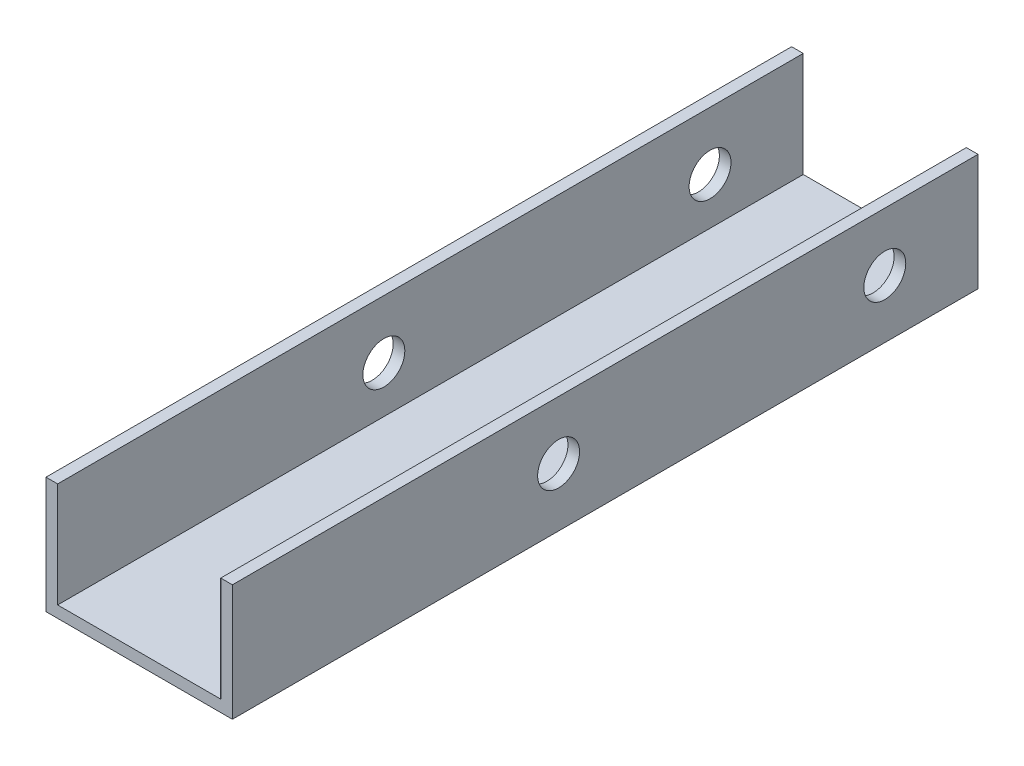
SolidWorks part; units mm, degrees
ref_plane "Ön Düzlem" through (0, 0, 0) normal (0, 0, 1) x (1, 0, 0)
ref_plane "Üst Düzlem" through (0, 0, 0) normal (0, 1, 0) x (1, 0, 0)
ref_plane "Sağ Düzlem" through (0, 0, 0) normal (1, 0, 0) x (0, 0, -1)
sketch "Çizim1" plane through (0, 0, 0) normal (0, 0, 1) x (1, 0, 0)
  line L0 (0, 0) -> (80, 0)
  line L1 (0, 0) -> (0, 50)
  line L2 (0, 50) -> (5, 50)
  line L3 (5, 50) -> (5, 5)
  line L4 (5, 5) -> (75, 5)
  line L5 (80, 0) -> (80, 50)
  line L6 (80, 50) -> (75, 50)
  line L7 (75, 50) -> (75, 5)
  dimension "D1" = 50
  dimension "D2" = 80
  dimension "D3" = 5
  dimension "D4" = 45
  dimension "D5" = 70
extrude "Yükseklik-Ekstrüzyon1" add sketch "Çizim1" along normal blind 500
sketch "Çizim2" plane through (80, 0, 0) normal (1, 0, 0) x (0, 0, -1)
  line L0 (-500, 0) -> (-500, 50) construction
  circle A0 centre (-330, 25) radius 9
  circle A1 centre (-190, 25) radius 9
  dimension "D1" = 140
  dimension "D2" = 170
extrude "Kes-Ekstrüzyon1" cut sketch "Çizim2" against normal blind 100
sketch "Çizim4" plane through (0, 0, 0) normal (0, 0, -1) x (-1, 0, 0)
  line L8 (0, 0) -> (0, 50)
  line L9 (0, 50) -> (-5, 50)
  line L10 (-5, 50) -> (-5, 5)
  line L11 (-5, 5) -> (-75, 5)
  line L12 (-75, 5) -> (-75, 50)
  line L13 (-75, 50) -> (-80, 50)
  line L14 (-80, 50) -> (-80, 0)
  line L15 (-80, 0) -> (0, 0)
  line L16 (0, 0) -> (0, 50)
  line L17 (0, 50) -> (-5, 50)
  line L18 (-5, 50) -> (-5, 5)
  line L19 (-5, 5) -> (-75, 5)
  line L20 (-75, 5) -> (-75, 50)
  line L21 (-75, 50) -> (-80, 50)
  line L22 (-80, 50) -> (-80, 0)
  line L23 (-80, 0) -> (0, 0)
  dimension "D1" = 0
extrude "Kes-Ekstrüzyon3" cut sketch "Çizim4" against normal blind 150
sketch "Çizim5" plane through (0, 0, 500) normal (0, 0, 1) x (1, 0, 0)
  line L8 (0, 50) -> (0, 0)
  line L9 (0, 0) -> (80, 0)
  line L10 (80, 0) -> (80, 50)
  line L11 (80, 50) -> (75, 50)
  line L12 (75, 50) -> (75, 5)
  line L13 (75, 5) -> (5, 5)
  line L14 (5, 5) -> (5, 50)
  line L15 (5, 50) -> (0, 50)
  line L16 (0, 50) -> (0, 0)
  line L17 (0, 0) -> (80, 0)
  line L18 (80, 0) -> (80, 50)
  line L19 (80, 50) -> (75, 50)
  line L20 (75, 50) -> (75, 5)
  line L21 (75, 5) -> (5, 5)
  line L22 (5, 5) -> (5, 50)
  line L23 (5, 50) -> (0, 50)
  dimension "D1" = 0
extrude "Kes-Ekstrüzyon4" cut sketch "Çizim5" against normal blind 30
